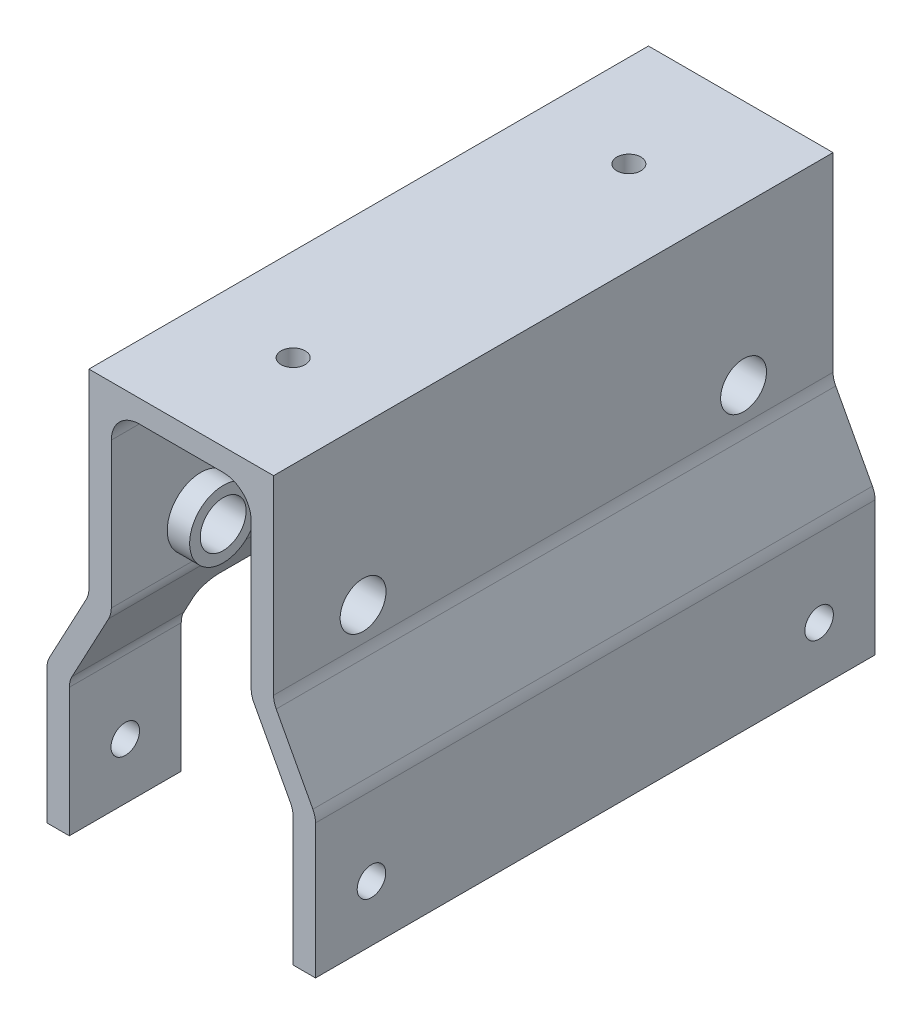
SolidWorks part; units mm, degrees
ref_plane "Front Plane" through (0, 0, 0) normal (0, 0, 1) x (1, 0, 0)
ref_plane "Top Plane" through (0, 0, 0) normal (0, 1, 0) x (1, 0, 0)
ref_plane "Right Plane" through (0, 0, 0) normal (1, 0, 0) x (0, 0, -1)
sketch "Sketch2" plane through (0, 0, 0) normal (0, 0, 1) x (1, 0, 0)
  line L0 (0, 0) -> (0, 23.9963)
  line L1 (0, 23.9963) -> (7.5, 38)
  line L2 (7.5, 38) -> (7.5, 70)
  line L3 (7.5, 70) -> (32.5, 70)
  line L4 (32.5, 70) -> (32.5, 38)
  line L5 (32.5, 38) -> (40, 23.9963)
  line L6 (40, 23.9963) -> (40, 0)
  line L7 (-4, 0) -> (-4, 25)
  line L8 (-4, 25) -> (3.5, 39.0037)
  line L9 (3.5, 39.0037) -> (3.5, 74)
  line L10 (3.5, 74) -> (36.5, 74)
  line L11 (36.5, 74) -> (36.5, 39.0037)
  line L12 (36.5, 39.0037) -> (44, 25)
  line L13 (44, 25) -> (44, 0)
  line L14 (-4, 0) -> (0, 0)
  line L15 (40, 0) -> (44, 0)
  dimension "D1" = 70
  dimension "D2" = 25
  dimension "D3" = 40
  dimension "D4" = 7.5
  dimension "D6" = 32
  dimension "D7" = 32
  dimension "D8" = 25
  dimension "D9" = 25
  dimension "D10" = 0
  dimension "D5" = 4
extrude "Boss-Extrude1" add sketch "Sketch2" along normal blind 100
sketch "Sketch3" plane through (32.5, 0, 0) normal (-1, 0, 0) x (0, 0, 1)
  line L0 (0, 70) -> (0, 38) construction
  line L1 (100, 70) -> (0, 70) construction
  line L2 (100, 70) -> (100, 38) construction
  circle A0 centre (84, 46) radius 6
  circle A1 centre (16, 46) radius 6
  dimension "D1" = 12
  dimension "D2" = 12
  dimension "D3" = 16
  dimension "D4" = 24
  dimension "D5" = 24
  dimension "D6" = 16
sketch "Sketch4" plane through (7.5, 0, 0) normal (1, 0, 0) x (0, 0, -1)
  circle A0 centre (-16, 46) radius 6 construction
  circle A1 centre (-84, 46) radius 6 construction
  circle A2 centre (-16, 46) radius 6
  circle A3 centre (-84, 46) radius 6
extrude "Boss-Extrude2" add sketch "Sketch3" along normal blind 4 contours A1 | A0
extrude "Boss-Extrude3" add sketch "Sketch4" along normal blind 4 contours A3 | A2
sketch "Sketch9" plane through (7.5, 0, 0) normal (1, 0, 0) x (0, 0, -1)
  circle A0 centre (-16, 46) radius 4.1
  circle A1 centre (-84, 46) radius 4.1
  dimension "D1" = 8.2
  dimension "D2" = 8.2
extrude "Cut-Extrude1" cut sketch "Sketch9" against normal through all both and the other way through all
sketch "Sketch10" plane through (44, 0, 0) normal (1, 0, 0) x (0, 0, -1)
  line L0 (-100, 0) -> (-100, 25) construction
  line L1 (-100, 0) -> (0, 0) construction
  line L2 (0, 0) -> (0, 25) construction
  circle A0 centre (-10, 10) radius 2.55
  circle A1 centre (-90, 10) radius 2.55
  dimension "D1" = 5.1
  dimension "D2" = 5.1
  dimension "D3" = 10
  dimension "D4" = 10
  dimension "D5" = 10
  dimension "D6" = 10
extrude "Cut-Extrude2" cut sketch "Sketch10" against normal through all both and the other way through all
sketch "Sketch13" plane through (-4, 0, 0) normal (-1, 0, 0) x (0, 0, 1)
  line L0 (100, 0) -> (0, 0) construction
  line L1 (20, 0) -> (20, 31.0037)
  line L2 (20, 31.0037) -> (80, 31.0037)
  line L3 (80, 31.0037) -> (80, 0)
  line L4 (80, 0) -> (20, 0)
  line L5 (100, 39.0037) -> (0, 39.0037) construction
  circle A0 centre (10, 10) radius 2.55 construction
  circle A1 centre (90, 10) radius 2.55 construction
  dimension "D1" = 10
  dimension "D2" = 10
  dimension "D3" = 8
extrude "Cut-Extrude5" cut sketch "Sketch13" against normal blind 24
fillet "Fillet1" radius 3 2 edges at (1.4842, 31.0037, 20) (1.4842, 31.0037, 80)
fillet "Fillet2" radius 5 2 edges at (7.5, 70, 50) (32.5, 70, 50)
fillet "Fillet3" radius 4 10 edges at (32.5, 38, 50) (40, 23.9963, 50) (44, 25, 50) (36.5, 39.0037, 50) (7.5, 38, 50) (-4, 25, 90) (-4, 25, 10) (3.5, 39.0037, 50) (0, 23.9963, 90) (0, 23.9963, 10)
sketch "Sketch15" plane through (0, 74, 0) normal (0, 1, 0) x (1, 0, 0)
  line L0 (36.5, -100) -> (3.5, -100) construction
  line L1 (3.5, 0) -> (3.5, -100) construction
  line L2 (3.5, -100) -> (3.5, 0) construction
  circle A0 centre (20, -20) radius 2.15
  circle A1 centre (20, -80) radius 2.15
  dimension "D1" = 4.3
  dimension "D2" = 4.3
  dimension "D3" = 60
  dimension "D4" = 20
  dimension "D5" = 16.5
  dimension "D6" = 16.5
extrude "Cut-Extrude6" cut sketch "Sketch15" against normal through all
